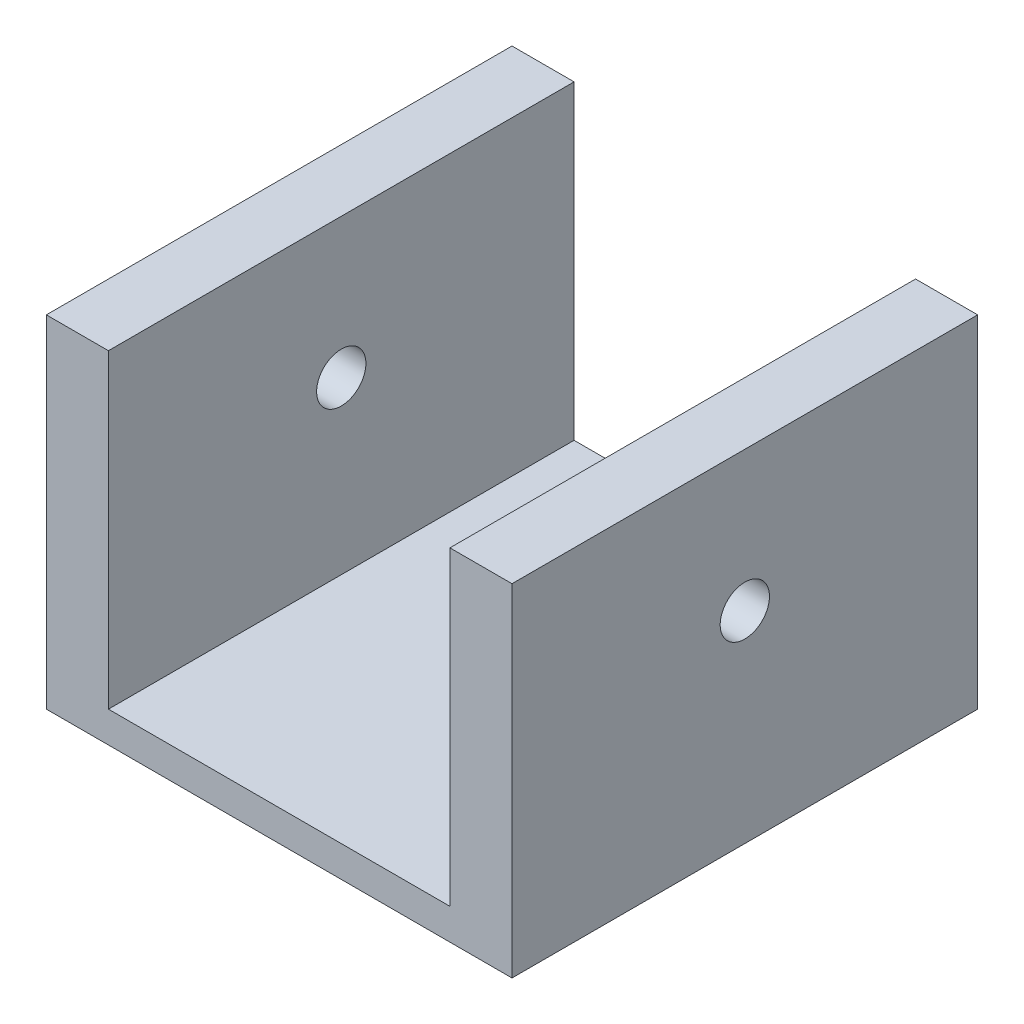
SolidWorks part; units mm, degrees
ref_plane "Front Plane" through (0, 0, 0) normal (0, 0, 1) x (1, 0, 0)
ref_plane "Top Plane" through (0, 0, 0) normal (0, 1, 0) x (1, 0, 0)
ref_plane "Right Plane" through (0, 0, 0) normal (1, 0, 0) x (0, 0, -1)
sketch "Sketch1" plane through (0, 0, 0) normal (0, 1, 0) x (1, 0, 0)
  line L1 (-75, -75) -> (75, -75)
  line L2 (-75, -75) -> (-75, 75)
  line L3 (-75, 75) -> (75, 75)
  line L4 (75, -75) -> (75, 75)
  line L5 (-75, -75) -> (75, 75) construction
  line L6 (-75, 75) -> (75, -75) construction
  point P0 (0, 0)
  dimension "D1" = 150
  dimension "D2" = 150
extrude "Boss-Extrude1" add sketch "Sketch1" along normal blind 10
sketch "Sketch2" plane through (0, 10, 0) normal (0, 1, 0) x (1, 0, 0)
  line L0 (75, 75) -> (-75, 75) construction
  line L1 (-75, -75) -> (-55, -75)
  line L2 (-75, -75) -> (-75, 75)
  line L3 (-75, 75) -> (-55, 75)
  line L4 (-55, -75) -> (-55, 75)
  line L6 (75, -75) -> (55, -75)
  line L7 (75, -75) -> (75, 75)
  line L8 (75, 75) -> (55, 75)
  line L9 (55, -75) -> (55, 75)
  dimension "D1" = 20
  dimension "D2" = 20
extrude "Boss-Extrude2" add sketch "Sketch2" along normal blind 100
sketch "Sketch3" plane through (75, 0, 0) normal (1, 0, 0) x (0, 0, -1)
  line L0 (0, 0) -> (0, 65) construction
  line L1 (-75, 0) -> (75, 0) construction
  circle A0 centre (0, 65) radius 7.9375
  dimension "D1" = 15.875
  dimension "D2" = 65
extrude "Cut-Extrude1" cut sketch "Sketch3" against normal through all
